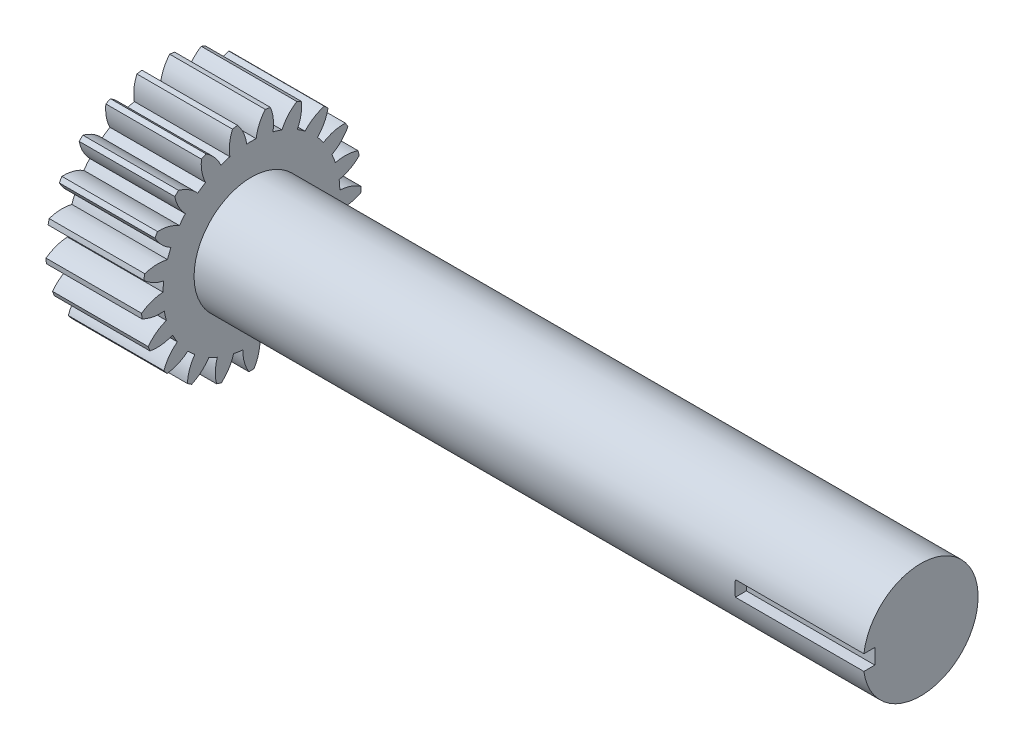
SolidWorks part; units mm, degrees
ref_plane "Plane1" through (0, 0, 0) normal (0, 0, 1) x (1, 0, 0)
ref_plane "Plane2" through (0, 0, 0) normal (0, 1, 0) x (1, 0, 0)
ref_plane "Plane3" through (0, 0, 0) normal (1, 0, 0) x (0, 0, -1)
sketch "HoldingSke" plane through (0, 0, 0) normal (0, 1, 0) x (1, 0, 0)
  line L0 (0, 0) -> (0.7469, -0.2867)
  line L1 (-15, 0) -> (100, 0) construction
  line L2 (0, 0) -> (-2.1039, 2.3779)
  line L3 (0, 0) -> (-11.863, 4.5341)
  line L4 (0, 0) -> (8.0624, 3.0949)
  line L5 (0, 0) -> (-46.8476, -17.4728)
  line L6 (0, 0) -> (-10.362, -6.9913)
  line L7 (-2.1039, 2.3779) -> (8.6586, 51.2059)
  line L8 (-76.2, 54.61) -> (-74.8, 54.61)
  line L9 (-71.009, 38.7566) -> (-53.1078, 45.2721)
  line L10 (-76.2, 71.12) -> (104.1128, 71.12)
  line L11 (0, 0) -> (-12.5, 0)
  line L12 (-76.2, 101.6) -> (-76.155, 101.6)
  line L13 (24.9733, 27.94) -> (52.9518, 28.4284)
  line L14 (24.9733, 27.94) -> (24.9743, 27.94)
  line L15 (24.9733, 27.94) -> (100.4006, 29.5858)
  line L16 (-63.627, -1.25) -> (-12.827, -1.25)
  circle A0 centre (0, 0) radius 4
  circle A1 centre (0, 0) radius 11.5615
  circle A2 centre (0, 0) radius 37.5
  circle A3 centre (0, 0) radius 4
  dimension "MHD" = 23.123
  dimension "Hub_dia" = 75
  dimension "Bore" = 8
  dimension "MBD" = 8
  dimension "Num_teeth" = 21
  dimension "Pitch" = 0.8
  dimension "Overall_len" = 50
  dimension "Show_teeth" = 21
  dimension "Thickness" = 12.5
  dimension "OAL" = 50.0001
  dimension "T_dim" = 1.4
  dimension "Ap" = 20
  dimension "H" = 19.05
  dimension "Pitch_radius" = 180.3128
  dimension "Width" = 12.5
  dimension "Backlash" = 0.045
  dimension "Addendum_fac" = 1
  dimension "Dedendum_fac" = 1.25
  dimension "Clearance_fac" = 0.25
  dimension "Dedendum_add" = 0.001
  dimension "Module" = 1.25
sketch "BasProSke" plane through (0, 0, 0) normal (0, 1, 0) x (1, 0, 0)
  line L0 (-10, 0) -> (60, 0) construction
  line L1 (0, 0) -> (0, 14.375)
  line L2 (0, 0) -> (12.5, 0)
  line L3 (12.5, 0) -> (12.5, 14.375)
  line L4 (12.5, 14.375) -> (0, 14.375)
  dimension "Thickness" = 12.5
  dimension "Diameter" = 28.75
revolve "Base-Revolve" add sketch "BasProSke" angle 360 about L0
sketch "TooCutSke" plane through (0, 0, 0) normal (1, 0, 0) x (0, 0, -1)
  line L1 (0, 0) -> (0, 107) construction
  line L2 (0, 0) -> (-1.0595, 13.0822) construction
  line L3 (0, 0) -> (-3.9031, 25.8954) construction
  line L4 (-1.0595, 13.0822) -> (-1.9516, 12.9477) construction
  arc A0 (0.6153, 11.5451) -> (-0.6153, 11.5451) centre (0, 0) ccw
  arc A1 (1.8309, 14.2835) -> (-1.8309, 14.2835) centre (0, 0) ccw
  circle A2 centre (0, 0) radius 13.125 construction
  circle A3 centre (0, 0) radius 12.3335 construction
  arc A4 (-0.6153, 11.5451) -> (-1.8309, 14.2835) centre (-5.822, 10.8728) ccw
  arc A5 (1.8309, 14.2835) -> (0.6153, 11.5451) centre (5.822, 10.8728) ccw
  dimension "Root_dia" = 23.123
  dimension "Overcut_dia" = 28.8008
  dimension "Pitch_dia" = 26.25
  dimension "Base_dia" = 24.6669
  dimension "Flank_rad" = 5.25
  dimension "Half_ang" = 8.571
  dimension "Half_CT" = 0.9021
extrude "ToothCut" cut sketch "TooCutSke" along normal through all
fillet "Breaks" [suppressed] radius 0.025
fillet "RootFillets" [suppressed] radius 0.3135
pattern_circular "TeethCuts" count 21 every 17.143 about axis through (-10, 0, 0) along (1, 0, 0) of "ToothCut", "RootFillets", "Breaks"
sketch "HubNeaOneSke" plane through (0, 0, 0) normal (-1, 0, 0) x (0, 0, 1)
  circle A0 centre (0, 0) radius 11.5615
  dimension "Diameter" = 23.123
extrude "HubNearOne" [suppressed] add sketch "HubNeaOneSke" along normal blind 37.5001
sketch "HubNeaBotSke" plane through (0, 0, 0) normal (-1, 0, 0) x (0, 0, 1)
  circle A0 centre (0, 0) radius 11.5615
  dimension "Diameter" = 23.123
extrude "HubNearBoth" [suppressed] add sketch "HubNeaBotSke" along normal blind 18.75
ref_plane "FarPln" through (12.5, 0, 0) normal (1, 0, 0) x (0, 0, -1)
sketch "HubFarSke" plane through (12.5, 0, 0) normal (1, 0, 0) x (0, 0, -1)
  circle A0 centre (0, 0) radius 11.5615
  dimension "Diameter" = 23.123
extrude "HubFar" [suppressed] add sketch "HubFarSke" along normal blind 18.75
sketch "BorSke" plane through (0, 0, 0) normal (1, 0, 0) x (0, 0, -1)
  circle A0 centre (0, 0) radius 4
  dimension "Diameter" = 8
extrude "Bore" cut sketch "BorSke" along normal mid plane 100.0001
sketch "KeySke" plane through (0, 0, 0) normal (1, 0, 0) x (0, 0, -1)
  line L0 (-1.5, 0) -> (-1.5, 5.4)
  line L1 (-1.5, 5.4) -> (1.5, 5.4)
  line L2 (1.5, 5.4) -> (1.5, 0)
  line L3 (0, 0) -> (0, 34) construction
  line L4 (-1.5, 0) -> (1.5, 0)
  dimension "Offset" = 5.4
  dimension "Width" = 3
extrude "Keyway" [suppressed] cut sketch "KeySke" along normal mid plane 100.0001
pattern_circular "Keyway2" [suppressed] count 2 every 90 about axis through (-10, 0, 0) along (1, 0, 0)
sketch "Sketch1" plane through (0, 0, 0) normal (-1, 0, 0) x (0, 0, 1)
  circle A2 centre (0, 0) radius 7.5
  dimension "D1" = 15
extrude "Boss-Extrude1" add sketch "Sketch1" against normal blind 100
sketch "Sketch2" plane through (100, 0, 0) normal (1, 0, 0) x (0, 0, -1)
  line L1 (-9, -1) -> (-6, -1)
  line L2 (-9, -1) -> (-9, 1)
  line L3 (-9, 1) -> (-6, 1)
  line L4 (-6, -1) -> (-6, 1)
  line L5 (-9, -1) -> (-6, 1) construction
  line L6 (-9, 1) -> (-6, -1) construction
  circle A0 centre (0, 0) radius 7.5 construction
  circle A1 centre (0, 0) radius 7.5 construction
  point P0 (-7.5, 0)
  dimension "D1" = 3
  dimension "D2" = 1
extrude "Cut-Extrude1" cut sketch "Sketch2" against normal blind 16.8
equation "' \"Module@HoldingSke\" = 6.35"
equation "' \"Num_teeth@HoldingSke\" = 12"
equation "' \"Ap@HoldingSke\" =  20"
equation "' \"Ap@HoldingSke\" = 20"
equation "' \"Width@HoldingSke\" = 0.5 * 25.4"
equation "' \"Hub_dia@HoldingSke\"= 1 * 25.4"
equation "' \"Hub_dia@HoldingSke\" = 1 * 25.4"
equation "' \"Overall_len@HoldingSke\" = 1.0 * 25.4"
equation "' \"Bore@HoldingSke\" = 0.75 * 25.4"
equation "' \"T_dim@HoldingSke\" = 0.1 * 25.4"
equation "' \"Width@KeySke\" = 0.25 * 25.4"
equation "' \"Show_teeth@HoldingSke\" = 13"
equation "' \"Backlash@HoldingSke\" = 0.009 * 25.4"
equation "' \"Addendum_fac@HoldingSke\" = 1.0"
equation "' \"Dedendum_fac@HoldingSke\" = 1.25"
equation "' \"Dedendum_add@HoldingSke\" = 0.00005 * 25.4"
equation "' \"Clearance_fac@HoldingSke\" = 0.25"
equation "\"Pitch@HoldingSke\" = 1 / \"Module@HoldingSke\""
equation "\"Overcut_dia@TooCutSke\" = (\"Num_teeth@HoldingSke\" + 2 * \"Addendum_fac@HoldingSke\") / \"Pitch@HoldingSke\" + 0.002 * 25.4"
equation "\"Pitch_dia@TooCutSke\" = \"Num_teeth@HoldingSke\" / \"Pitch@HoldingSke\""
equation "\"Base_dia@TooCutSke\" = \"Num_teeth@HoldingSke\" / \"Pitch@HoldingSke\" * cos((\"Ap@HoldingSke\"  * 3.14159265 / 180))"
equation "\"Root_dia@TooCutSke\" = (\"Num_teeth@HoldingSke\" + 2) / \"Pitch@HoldingSke\" - 2 * (\"Addendum_fac@HoldingSke\" + \"Dedendum_fac@HoldingSke\") / \"Pitch@HoldingSke\" - \"Dedendum_add@HoldingSke\" * 2"
equation "\"Half_ang@TooCutSke\" = 180 / \"Num_teeth@HoldingSke\""
equation "\"Half_CT@TooCutSke\" = \"Num_teeth@HoldingSke\" / \"Pitch@HoldingSke\" * sin((3.14159265 / 2 / \"Num_teeth@HoldingSke\")) / 2 - 7 * \"Backlash@HoldingSke\" / 4"
equation "\"Flank_rad@TooCutSke\" = \"Num_teeth@HoldingSke\" / \"Pitch@HoldingSke\" / 5"
equation "\"Radius@RootFillets\" = \"Clearance_fac@HoldingSke\" / \"Pitch@HoldingSke\" + \"Dedendum_add@HoldingSke\""
equation "\"Break_rad@Breaks\" = 0.02 / \"Pitch@HoldingSke\""
equation "\"Thickness@HoldingSke\" = \"Width@HoldingSke\""
equation "\"OAL@HoldingSke\" = \"Thickness@HoldingSke\""
equation "\"MHD@HoldingSke\" = (\"Num_teeth@HoldingSke\" + 2) / \"Pitch@HoldingSke\" - 2 * (\"Addendum_fac@HoldingSke\" + \"Dedendum_fac@HoldingSke\")  / \"Pitch@HoldingSke\" - \"Dedendum_add@HoldingSke\" * 2"
equation "\"MBD@HoldingSke\" = (\"Num_teeth@HoldingSke\" + 2) / \"Pitch@HoldingSke\" - 2 * (\"Addendum_fac@HoldingSke\" + \"Dedendum_fac@HoldingSke\")  / \"Pitch@HoldingSke\" - \"Dedendum_add@HoldingSke\" * 2 - 0.002 * 25.4"
equation "\"MHD@HoldingSke\" = ((sgn( \"MHD@HoldingSke\" - \"Hub_dia@HoldingSke\" )-1)*( \"MHD@HoldingSke\" - \"Hub_dia@HoldingSke\" ))/-2+ \"Hub_dia@HoldingSke\""
equation "\"MBD@HoldingSke\" = ((sgn( \"MBD@HoldingSke\" - \"Bore@HoldingSke\" )-1)*( \"MBD@HoldingSke\" - \"Bore@HoldingSke\" ))/-2+ \"Bore@HoldingSke\""
equation "\"OAL@HoldingSke\" = ((sgn( \"OAL@HoldingSke\" - \"Overall_len@HoldingSke\" )+1)*( \"OAL@HoldingSke\" - \"Overall_len@HoldingSke\" ))/2 + \"Overall_len@HoldingSke\" + 0.000002 * 25.4"
equation "\"Num_teeth@TeethCuts\" = int( \"Show_teeth@HoldingSke\" ) + 1"
equation "\"Num_teeth@TeethCuts\" = ((sgn( \"Num_teeth@TeethCuts\" - \"Num_teeth@HoldingSke\" )-1)*( \"Num_teeth@TeethCuts\" - \"Num_teeth@HoldingSke\" ))/-2+ \"Num_teeth@HoldingSke\""
equation "\"Num_teeth@TeethCuts\" = ((sgn( \"Num_teeth@TeethCuts\" - 2.0)+1)*( \"Num_teeth@TeethCuts\" - 2.0))/2 +2.0"
equation "\"Angle@TeethCuts\" = 360.0 / \"Num_teeth@HoldingSke\""
equation "\"Diameter@BasProSke\" = (\"Num_teeth@HoldingSke\" + 2 * \"Addendum_fac@HoldingSke\") / \"Pitch@HoldingSke\""
equation "\"Thickness@BasProSke\"  = \"Thickness@HoldingSke\""
equation "' \"Fillet_rad@BasProSke\" =  \"Thickness@HoldingSke\" * 0.05"
equation "' \"Fillet_rad@BasProSke\" = \"Thickness@HoldingSke\" * 0.05"
equation "\"MHD@HoldingSke\" = ((sgn( \"MHD@HoldingSke\" - \"Root_dia@TooCutSke\" )-1)*( \"MHD@HoldingSke\" - \"Root_dia@TooCutSke\" ))/-2+ \"Root_dia@TooCutSke\""
equation "\"Diameter@HubNeaOneSke\" = \"MHD@HoldingSke\""
equation "\"Length@HubNearOne\" = \"OAL@HoldingSke\" - \"Thickness@BasProSke\""
equation "\"Diameter@HubNeaBotSke\" = \"MHD@HoldingSke\""
equation "\"Length@HubNearBoth\" = ( \"OAL@HoldingSke\" - \"Thickness@BasProSke\" ) / 2.0"
equation "\"Thickness@FarPln\" = \"Thickness@BasProSke\""
equation "\"Diameter@HubFarSke\" = \"MHD@HoldingSke\""
equation "\"Length@HubFar\" = ( \"OAL@HoldingSke\" - \"Thickness@BasProSke\" ) / 2.0"
equation "\"Diameter@BorSke\" = \"MBD@HoldingSke\""
equation "\"D1@Bore\" = \"OAL@HoldingSke\" * 2.0"
equation "\"D1@Keyway\" = \"OAL@HoldingSke\" * 2.0"
equation "\"Offset@KeySke\" = \"T_dim@HoldingSke\" + \"MBD@HoldingSke\" / 2.0"
